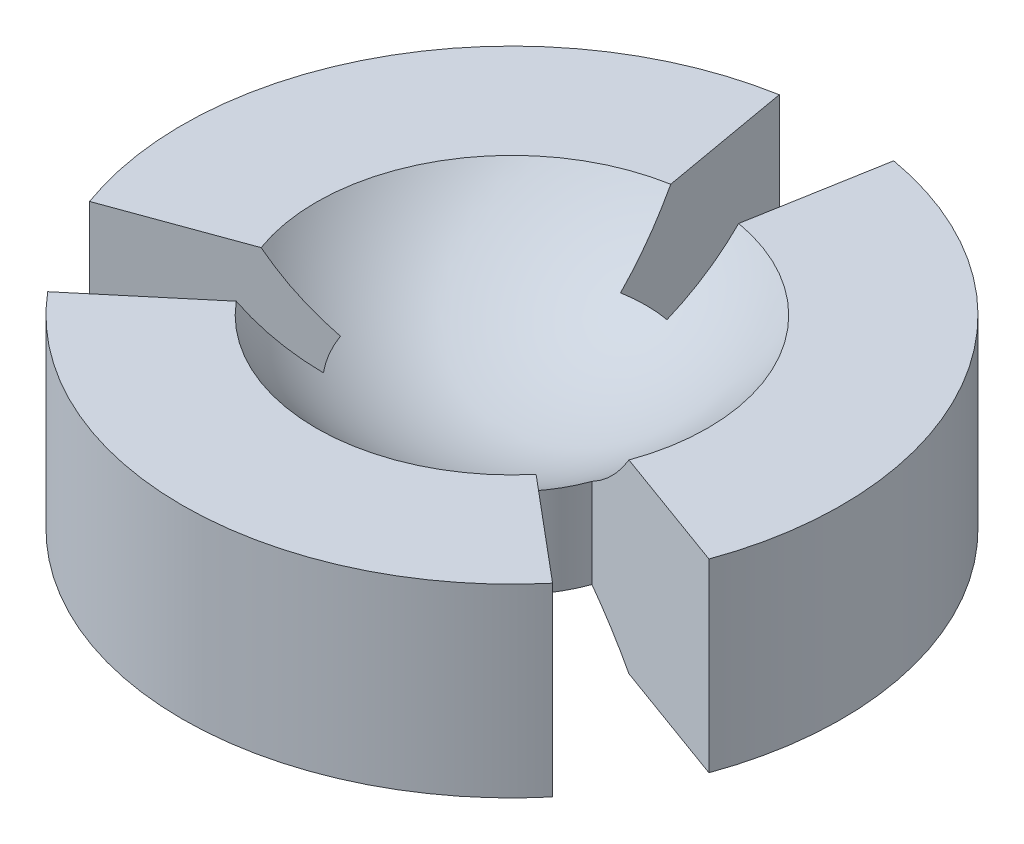
SolidWorks part; units mm, degrees
ref_plane "前视基准面" through (0, 0, 0) normal (0, 0, 1) x (1, 0, 0)
ref_plane "上视基准面" through (0, 0, 0) normal (0, 1, 0) x (1, 0, 0)
ref_plane "右视基准面" through (0, 0, 0) normal (1, 0, 0) x (0, 0, -1)
sketch "草图1" plane through (0, 0, 0) normal (0, 0, 1) x (1, 0, 0)
  line L17 (0, 0) -> (0, 7.1) construction
  line L18 (0, 3.6) -> (-3.6, 3.6) construction
  line L19 (0, 3.6) -> (-3.1177, 5.4) construction
  line L20 (-3.1177, 5.4) -> (0, 5.4) construction
  line L23 (0, 5.6) -> (-2.925, 5.6) construction
  line L24 (0, 7.1) -> (0, 10.55) construction
  line L25 (-2.925, 5.6) -> (-4.925, 5.6)
  line L26 (-4.925, 5.6) -> (-4.925, 8.3667)
  line L27 (-2.925, 8.3667) -> (-4.925, 8.3667)
  line L28 (0, 6.9) -> (0, 6.6)
  circle A11 centre (0, 10.55) radius 3.45 construction
  arc A12 (-3.1177, 5.4) -> (0, 0) centre (0, 3.6) ccw construction
  arc A14 (-2.925, 8.3667) -> (0, 6.9) centre (0, 10.55) ccw
  arc A15 (-2.925, 5.6) -> (0, 6.6) centre (0, 1.8221) cw
  point P2 (0, 3.6)
  point P17 (0, 6.6)
  dimension "D1" = 7.1
  dimension "D4" = 0.2
  dimension "D3" = 30
  dimension "D8" = 2
  dimension "D7" = 0.2
  dimension "D2" = 3.6
  dimension "D5" = 3.45
  dimension "D6" = 2
  dimension "D9" = 1
revolve "旋转2" add sketch "草图1" angle 360 about L28
sketch "草图2" plane through (0, 8.3667, 0) normal (0, 1, 0) x (1, 0, 0)
  line L0 (0, 0) -> (0, 2) construction
  line L3 (-0.3473, 1.9696) -> (-1.7365, 9.8481)
  line L4 (0.3473, 1.9696) -> (1.7365, 9.8481)
  line L5 (1.8794, -0.684) -> (9.3969, -3.4202)
  line L6 (1.5321, -1.2856) -> (7.6604, -6.4279)
  line L7 (0, 0) -> (1.7321, -1) construction
  line L8 (-1.5321, -1.2856) -> (-7.6604, -6.4279)
  line L9 (-1.8794, -0.684) -> (-9.3969, -3.4202)
  line L10 (0, 0) -> (-1.7321, -1) construction
  arc A2 (1.7365, 9.8481) -> (-1.7365, 9.8481) centre (0, 0) ccw
  arc A3 (0.3473, 1.9696) -> (-0.3473, 1.9696) centre (0, 0) ccw
  arc A4 (7.6604, -6.4279) -> (9.3969, -3.4202) centre (0, 0) ccw
  arc A5 (1.5321, -1.2856) -> (1.8794, -0.684) centre (0, 0) ccw
  arc A6 (-9.3969, -3.4202) -> (-7.6604, -6.4279) centre (0, 0) ccw
  arc A7 (-1.8794, -0.684) -> (-1.5321, -1.2856) centre (0, 0) ccw
  point P19 (0, 0)
  dimension "D1" = 10
  dimension "D2" = 10
  dimension "D4" = 10
  dimension "D3" = 3
extrude "切除-拉伸1" cut sketch "草图2" against normal through all
